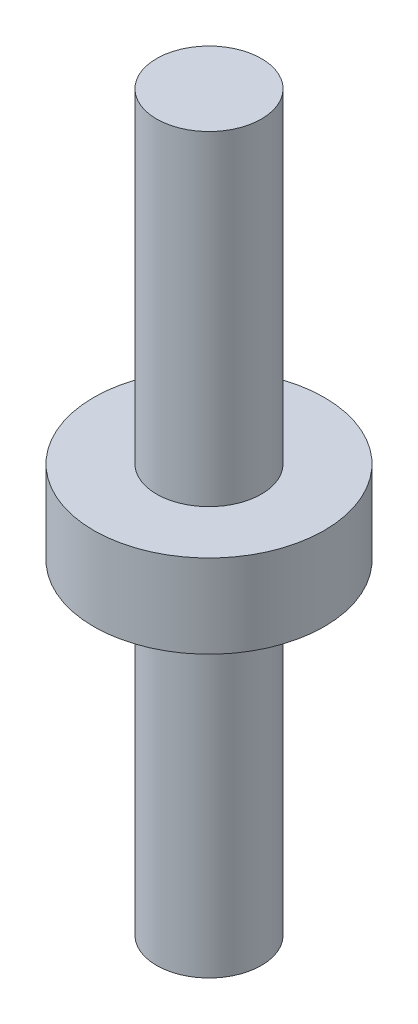
SolidWorks part; units mm, degrees
ref_plane "前视基准面" through (0, 0, 0) normal (0, 0, 1) x (1, 0, 0)
ref_plane "上视基准面" through (0, 0, 0) normal (0, 1, 0) x (1, 0, 0)
ref_plane "右视基准面" through (0, 0, 0) normal (1, 0, 0) x (0, 0, -1)
sketch "草图1" plane through (0, 0, 0) normal (0, 1, 0) x (1, 0, 0)
  circle A0 centre (0, 0) radius 5
extrude "凸台-拉伸1" add sketch "草图1" along normal blind 31
sketch "Sketch1" plane through (0, 31, 0) normal (0, 1, 0) x (1, 0, 0)
  circle A0 centre (0, 0) radius 11
extrude "Boss-Extrude1" add sketch "Sketch1" along normal blind 7.95
sketch "Sketch2" plane through (0, 38.95, 0) normal (0, 1, 0) x (1, 0, 0)
  circle A0 centre (0, 0) radius 5
extrude "Boss-Extrude2" add sketch "Sketch2" along normal blind 31
